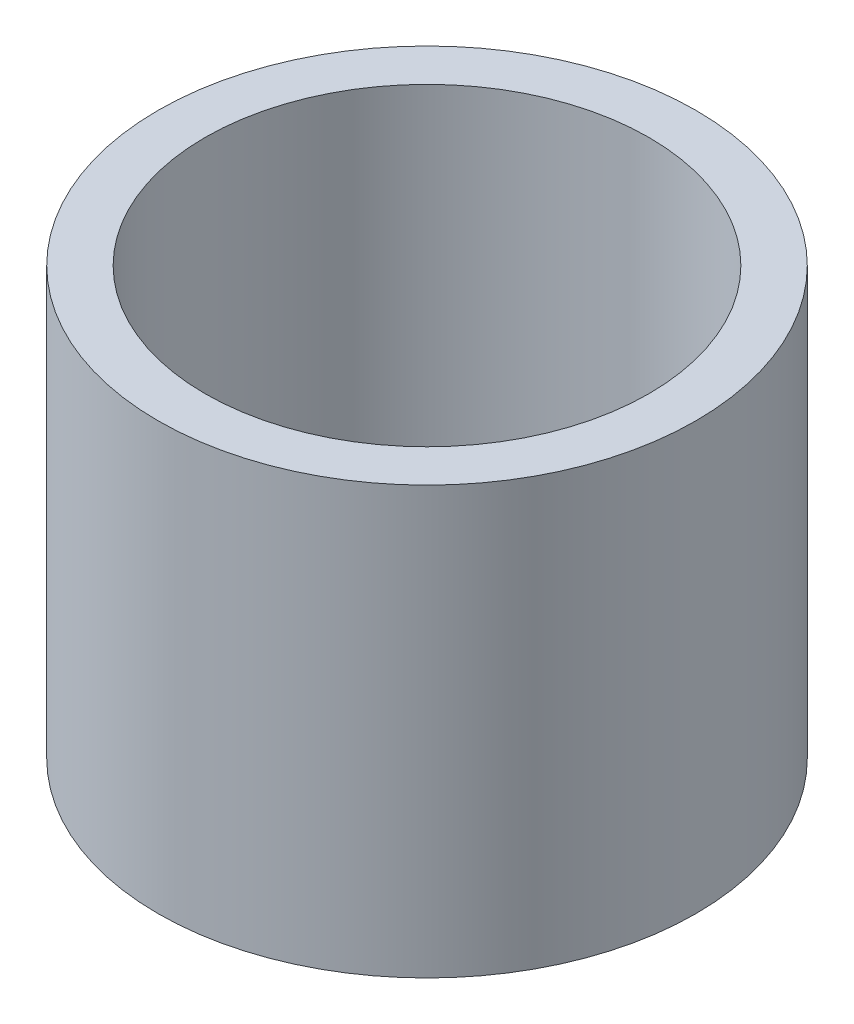
SolidWorks part; units mm, degrees
ref_plane "정면" through (0, 0, 0) normal (0, 0, 1) x (1, 0, 0)
ref_plane "윗면" through (0, 0, 0) normal (0, 1, 0) x (1, 0, 0)
ref_plane "우측면" through (0, 0, 0) normal (1, 0, 0) x (0, 0, -1)
sketch "스케치1" plane through (0, 0, 0) normal (0, 1, 0) x (1, 0, 0)
  circle A0 centre (0, 0) radius 12.6
  dimension "D1" = 25.2
extrude "보스-돌출1" add sketch "스케치1" along normal blind 20
shell "쉘1" thickness 2.2
